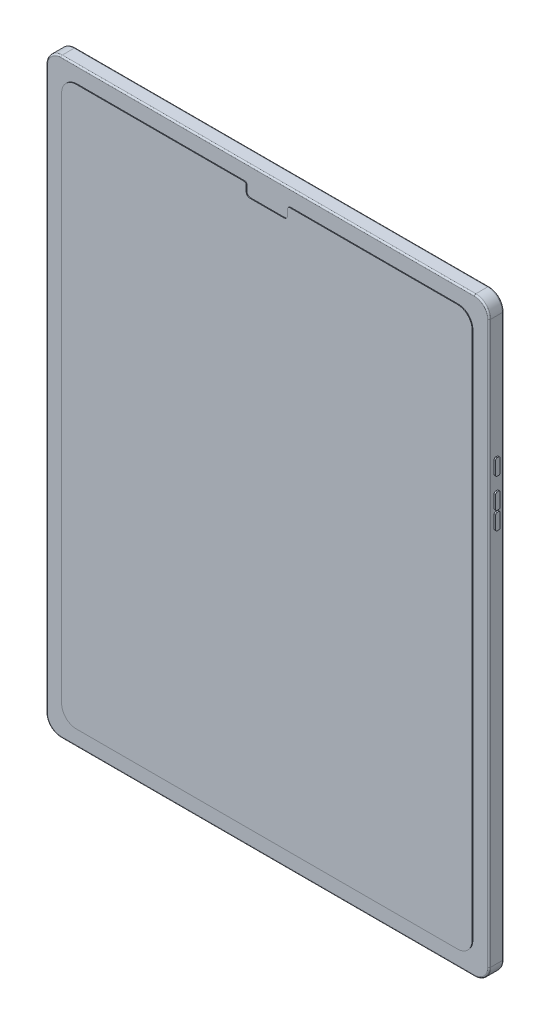
SolidWorks part; units mm, degrees
ref_plane "Front Plane" through (0, 0, 0) normal (0, 0, 1) x (1, 0, 0)
ref_plane "Top Plane" through (0, 0, 0) normal (0, 1, 0) x (1, 0, 0)
ref_plane "Right Plane" through (0, 0, 0) normal (1, 0, 0) x (0, 0, -1)
sketch "Sketch1" plane through (0, 0, 0) normal (0, 0, 1) x (1, 0, 0)
  line L1 (-15, 20) -> (15, 20)
  line L2 (-15, 20) -> (-15, -20)
  line L3 (-15, -20) -> (15, -20)
  line L4 (15, 20) -> (15, -20)
  line L5 (-15, 20) -> (15, -20) construction
  line L6 (-15, -20) -> (15, 20) construction
  point P0 (0, 0)
  dimension "D1" = 30
  dimension "D2" = 40
extrude "Boss-Extrude1" add sketch "Sketch1" along normal blind 1
fillet "Fillet1" radius 1 4 edges at (15, -20, 0.5) (-15, -20, 0.5) (-15, 20, 0.5) (15, 20, 0.5)
fillet "Fillet2" radius 0.1 16 edges at (14.7071, 19.7071, 0) (15, 0, 0) (14.7071, -19.7071, 0) (0, -20, 0) (-14.7071, -19.7071, 0) (-15, 0, 0) (-14.7071, 19.7071, 0) (14.7071, 19.7071, 1) (15, 0, 1) (14.7071, -19.7071, 1) (0, -20, 1) (-14.7071, -19.7071, 1) (-15, 0, 1) (-14.7071, 19.7071, 1) (0, 20, 0) (0, 20, 1)
sketch "Sketch2" plane through (0, 0, 1) normal (0, 0, 1) x (1, 0, 0)
  line L0 (-1.55, 18.9) -> (-12.9, 18.9)
  line L7 (-1.4, 18.75) -> (-1.4, 18.35)
  line L8 (13.9, -18.9) -> (13.9, 18.9)
  line L9 (13.9, 18.9) -> (-13.9, 18.9)
  line L10 (-13.9, 18.9) -> (-13.9, -18.9)
  line L11 (-13.9, -18.9) -> (13.9, -18.9)
  line L12 (13.9, -17.9) -> (13.9, 17.9)
  line L13 (12.9, 18.9) -> (1.55, 18.9)
  line L14 (-13.9, 17.9) -> (-13.9, -17.9)
  line L15 (-12.9, -18.9) -> (12.9, -18.9)
  line L16 (-1.15, 18.1) -> (1.15, 18.1)
  line L17 (1.4, 18.75) -> (1.4, 18.35)
  arc A0 (1.15, 18.1) -> (1.4, 18.35) centre (1.15, 18.35) ccw
  arc A1 (-1.15, 18.1) -> (-1.4, 18.35) centre (-1.15, 18.35) cw
  arc A2 (1.4, 18.75) -> (1.55, 18.9) centre (1.55, 18.75) cw
  arc A3 (-1.4, 18.75) -> (-1.55, 18.9) centre (-1.55, 18.75) ccw
  arc A4 (-13.9, -17.9) -> (-12.9, -18.9) centre (-12.9, -17.9) ccw
  arc A5 (-12.9, 18.9) -> (-13.9, 17.9) centre (-12.9, 17.9) ccw
  arc A6 (13.9, 17.9) -> (12.9, 18.9) centre (12.9, 17.9) ccw
  arc A7 (13.9, -17.9) -> (12.9, -18.9) centre (12.9, -17.9) cw
  point P24 (-1.4, 18.1)
  point P27 (1.4, 18.9)
  point P30 (-1.4, 18.9)
  dimension "D2" = 1
  dimension "D6" = 0.25
  dimension "D7" = 0.15
  dimension "D3" = 11.5
  dimension "D4" = 11.5
  dimension "D5" = 0.8
  dimension "D1" = 1
extrude "Boss-Extrude3" add sketch "Sketch2" along normal blind 0.05
sketch "Sketch3" plane through (15, 0, 0) normal (1, 0, 0) x (0, 0, -1)
  line L0 (-0.657, 8.6583) -> (-0.657, 7.7741)
  line L1 (-0.557, 10.7583) -> (-0.4557, 10.7583)
  line L2 (-0.657, 10.6583) -> (-0.657, 9.7741)
  line L3 (-0.557, 9.6741) -> (-0.4557, 9.6741)
  line L4 (-0.3557, 10.6583) -> (-0.3557, 9.7741)
  line L5 (-0.657, 10.7583) -> (-0.3557, 9.6741) construction
  line L6 (-0.657, 9.6741) -> (-0.3557, 10.7583) construction
  line L7 (-0.557, 8.7583) -> (-0.4557, 8.7583)
  line L8 (-0.3557, 8.6583) -> (-0.3557, 7.7741)
  line L9 (-0.557, 7.6741) -> (-0.4557, 7.6741)
  line L10 (-0.657, 7.4583) -> (-0.657, 6.5741)
  line L11 (-0.557, 6.4741) -> (-0.4557, 6.4741)
  line L12 (-0.3557, 7.4583) -> (-0.3557, 6.5741)
  line L13 (-0.557, 7.5583) -> (-0.4557, 7.5583)
  arc A0 (-0.4557, 10.7583) -> (-0.3557, 10.6583) centre (-0.4557, 10.6583) cw
  arc A1 (-0.657, 9.7741) -> (-0.557, 9.6741) centre (-0.557, 9.7741) ccw
  arc A2 (-0.557, 10.7583) -> (-0.657, 10.6583) centre (-0.557, 10.6583) ccw
  arc A3 (-0.4557, 9.6741) -> (-0.3557, 9.7741) centre (-0.4557, 9.7741) ccw
  arc A4 (-0.557, 8.7583) -> (-0.657, 8.6583) centre (-0.557, 8.6583) ccw
  arc A5 (-0.657, 7.7741) -> (-0.557, 7.6741) centre (-0.557, 7.7741) ccw
  arc A6 (-0.4557, 8.7583) -> (-0.3557, 8.6583) centre (-0.4557, 8.6583) cw
  arc A7 (-0.4557, 7.6741) -> (-0.3557, 7.7741) centre (-0.4557, 7.7741) ccw
  arc A8 (-0.657, 6.5741) -> (-0.557, 6.4741) centre (-0.557, 6.5741) ccw
  arc A9 (-0.4557, 6.4741) -> (-0.3557, 6.5741) centre (-0.4557, 6.5741) ccw
  arc A10 (-0.4557, 7.5583) -> (-0.3557, 7.4583) centre (-0.4557, 7.4583) cw
  arc A11 (-0.557, 7.5583) -> (-0.657, 7.4583) centre (-0.557, 7.4583) ccw
  point P0 (-0.5064, 10.2162)
  dimension "D1" = 0.1
  dimension "D2" = 2
  dimension "D3" = 2
extrude "Boss-Extrude4" add sketch "Sketch3" along normal blind 0.1
sketch "Sketch4" plane through (-15, 0, 0) normal (-1, 0, 0) x (0, 0, 1)
  circle A0 centre (0.5, -17.61) radius 0.05
  circle A1 centre (0.5, -17.4537) radius 0.05
  point P4 (0.5, -17.4537)
  dimension "D1" = 0.1
  dimension "D2" = 0.1
extrude "Cut-Extrude1" cut sketch "Sketch4" against normal blind 0.1
sketch "Sketch5" plane through (0, -20, 0) normal (0, -1, 0) x (1, 0, 0)
  line L0 (-0.5, 0.4787) -> (0.5, 0.4787) construction
  line L1 (-0.5, 0.6971) -> (0.5, 0.6971)
  line L2 (-0.5, 0.2604) -> (0.5, 0.2604)
  arc A0 (-0.5, 0.6971) -> (-0.5, 0.2604) centre (-0.5, 0.4787) ccw
  arc A1 (0.5, 0.2604) -> (0.5, 0.6971) centre (0.5, 0.4787) ccw
  point P2 (0, 0.4787)
  point P7 (0, 0.5275)
  point P8 (0, 0.4787)
  dimension "D1" = 1
extrude "Cut-Extrude2" cut sketch "Sketch5" against normal blind 1.5
sketch "Sketch6" plane through (0, -20, 0) normal (0, -1, 0) x (1, 0, 0)
  line L0 (-14, 0.9) -> (-14, 0.1) construction
  line L1 (14, 0.1) -> (14, 0.9) construction
  circle A0 centre (-12, 0.477) radius 0.125
  circle A1 centre (-11.5, 0.477) radius 0.125
  circle A2 centre (-11, 0.477) radius 0.125
  circle A3 centre (-10.5, 0.477) radius 0.125
  circle A4 centre (-10, 0.477) radius 0.125
  circle A5 centre (12, 0.5) radius 0.125
  circle A6 centre (11.5, 0.5) radius 0.125
  circle A7 centre (11, 0.5) radius 0.125
  circle A8 centre (10.5, 0.5) radius 0.125
  circle A9 centre (10, 0.5) radius 0.125
  dimension "D1" = 0.25
  dimension "D2" = 2
  dimension "D4" = 0.25
  dimension "D5" = 2
  dimension "D3" = 5
  dimension "D6" = 5
extrude "Cut-Extrude3" cut sketch "Sketch6" against normal blind 1
sketch "Sketch7" plane through (0, -20, 0) normal (0, -1, 0) x (1, 0, 0)
  circle A0 centre (-3.2077, 0.5368) radius 0.2226
  circle A1 centre (-2.2792, 0.5368) radius 0.109
extrude "Cut-Extrude4" cut sketch "Sketch7" against normal blind 1
sketch "Sketch8" plane through (0, 0, 0) normal (0, 0, -1) x (-1, 0, 0)
  line L0 (-11.8251, 0) -> (11.8336, 0) construction
  text T0 "InnoCAD" font "Century Gothic" height 2.5
extrude "Boss-Extrude5" add sketch "Sketch8" along normal blind 0.02
sketch "Sketch9" plane through (0, 0, 0) normal (0, 0, -1) x (-1, 0, 0)
  circle A0 centre (12.2677, 17.6626) radius 1.0536
  point P2 (0, 0)
extrude "Boss-Extrude6" add sketch "Sketch9" along normal blind 0.5
fillet "Fillet3" radius 0.25 1 edges at (-13.3213, 17.6626, -0.5)
sketch "Sketch10" plane through (0, 0, 0) normal (0, 0, -1) x (-1, 0, 0)
  circle A0 centre (12.2677, 15.7685) radius 0.1951
extrude "Boss-Extrude7" add sketch "Sketch10" along normal blind 0.1
fillet "Fillet4" radius 0.05 1 edges at (-12.4629, 15.7685, -0.1)
